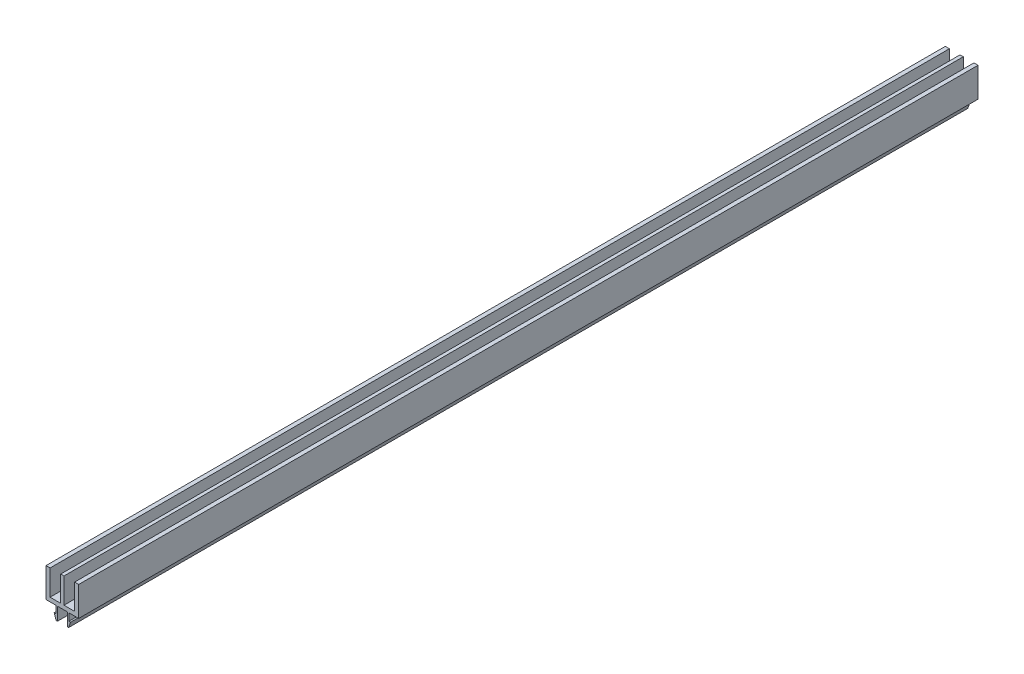
SolidWorks part; units mm, degrees
ref_plane "Plan de face" through (0, 0, 0) normal (0, 0, 1) x (1, 0, 0)
ref_plane "Plan de dessus" through (0, 0, 0) normal (0, 1, 0) x (1, 0, 0)
ref_plane "Plan de droite" through (0, 0, 0) normal (1, 0, 0) x (0, 0, -1)
ref_plane "Plan1" through (0, 0, 50) normal (0, 0, 1) x (1, 0, 0)
sketch "Esquisse1" plane through (0, 0, 50) normal (0, 0, 1) x (1, 0, 0)
  line L0 (-1, 2.5) -> (-7.5, 2.5)
  line L1 (-7.5, 2.5) -> (-7.5, 18)
  line L2 (-7.5, 18) -> (-10, 18)
  line L3 (-10, 18) -> (-10, 0)
  line L4 (-10, 0) -> (-4, 0)
  line L5 (-4, 0) -> (-4, -4.5)
  line L6 (-4, -4.5) -> (-5, -4.5)
  line L7 (-5, -4.5) -> (-3.75, -8)
  line L8 (-3.75, -8) -> (-3, -8)
  line L9 (-3, -8) -> (-3, 0)
  line L10 (-3, 0) -> (3, 0)
  line L11 (3, 0) -> (3, -8)
  line L12 (3, -8) -> (3.75, -8)
  line L13 (3.75, -8) -> (5, -4.5)
  line L14 (5, -4.5) -> (4, -4.5)
  line L15 (4, -4.5) -> (4, 0)
  line L16 (4, 0) -> (10, 0)
  line L17 (10, 0) -> (10, 18)
  line L18 (10, 18) -> (7.5, 18)
  line L19 (7.5, 18) -> (7.5, 2.5)
  line L20 (7.5, 2.5) -> (1, 2.5)
  line L21 (1, 2.5) -> (1, 18)
  line L22 (1, 18) -> (-1, 18)
  line L23 (-1, 18) -> (-1, 2.5)
extrude "Boss.-Extru.1" add sketch "Esquisse1" against normal blind 550
